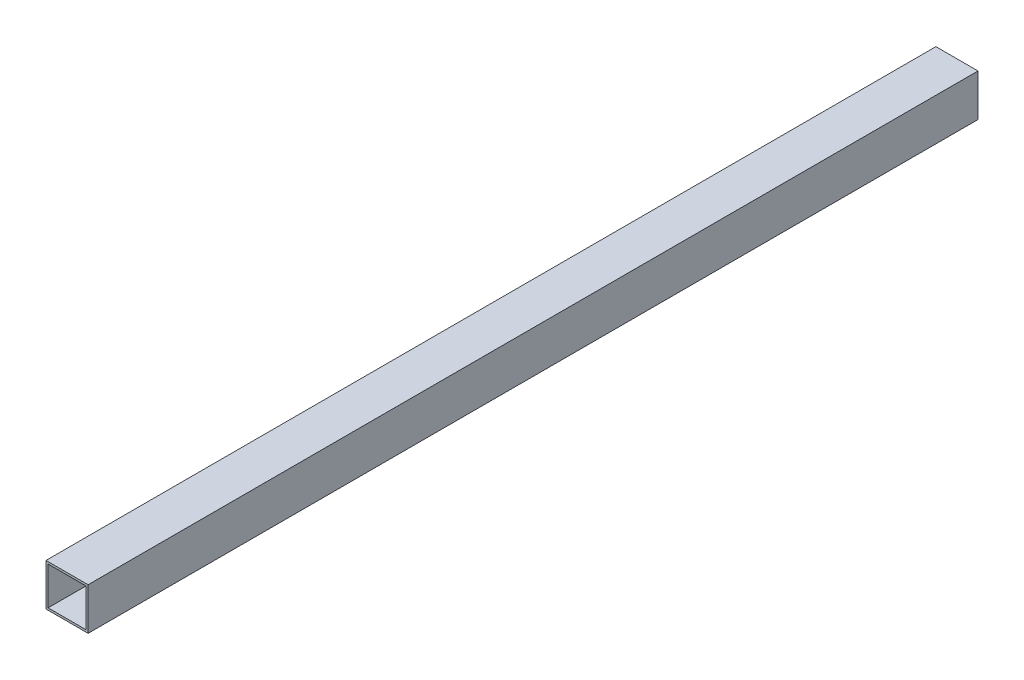
SolidWorks part; units mm, degrees
ref_plane "Front Plane" through (0, 0, 0) normal (0, 0, 1) x (1, 0, 0)
ref_plane "Top Plane" through (0, 0, 0) normal (0, 1, 0) x (1, 0, 0)
ref_plane "Right Plane" through (0, 0, 0) normal (1, 0, 0) x (0, 0, -1)
sketch "Sketch1" plane through (0, 0, 0) normal (0, 0, 1) x (1, 0, 0)
  line L1 (0, 0) -> (20, 0)
  line L2 (0, 0) -> (0, -20)
  line L3 (0, -20) -> (20, -20)
  line L4 (20, 0) -> (20, -20)
  line L5 (1, -19) -> (19, -19)
  line L6 (1, -19) -> (1, -1)
  line L7 (1, -1) -> (19, -1)
  line L8 (19, -19) -> (19, -1)
  line L9 (1, -19) -> (19, -1) construction
  line L10 (1, -1) -> (19, -19) construction
  point P5 (10, -10)
  dimension "D1" = 20
  dimension "D2" = 20
  dimension "D3" = 1
  dimension "D4" = 1
  dimension "D5" = 1
  dimension "D6" = 1
extrude "Boss-Extrude1" add sketch "Sketch1" along normal blind 422.68
